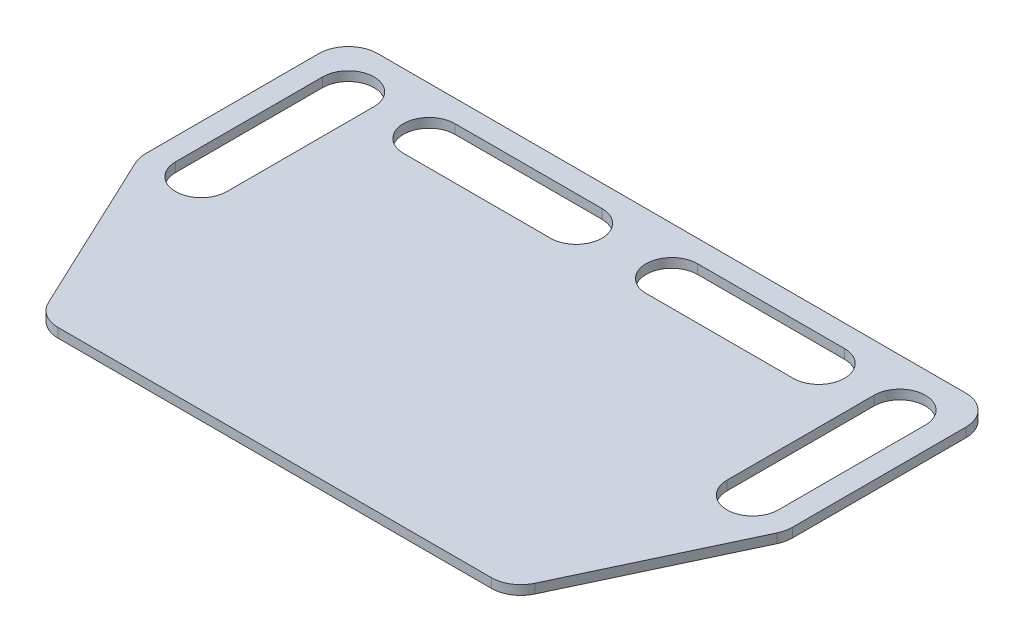
SolidWorks part; units mm, degrees
ref_plane "Front Plane" through (0, 0, 0) normal (0, 0, 1) x (1, 0, 0)
ref_plane "Top Plane" through (0, 0, 0) normal (0, 1, 0) x (1, 0, 0)
ref_plane "Right Plane" through (0, 0, 0) normal (1, 0, 0) x (0, 0, -1)
sketch "Sketch1" plane through (0, 0, 0) normal (0, 1, 0) x (1, 0, 0)
  line L0 (-187.5, 127.5) -> (-187.5, 27.5) construction
  line L1 (-147.3079, -110) -> (147.3079, -110)
  line L2 (-165.4043, -98.5159) -> (-218.0964, 13.4548)
  line L3 (-200, 160) -> (200, 160)
  line L4 (165.4043, -98.5159) -> (218.0964, 13.4548)
  line L5 (220, 21.9707) -> (220, 140)
  line L7 (-170, 127.5) -> (-170, 27.5)
  line L8 (-205, 127.5) -> (-205, 27.5)
  line L9 (-132.5, 127.5) -> (-32.5, 127.5) construction
  line L10 (-132.5, 145) -> (-32.5, 145)
  line L11 (-132.5, 110) -> (-32.5, 110)
  line L12 (-205, 77.5) -> (-170, 77.5) construction
  line L13 (-82.5, 110) -> (-82.5, 145) construction
  line L14 (-205, 77.5) -> (-220, 77.5) construction
  line L15 (-82.5, 145) -> (-82.5, 160) construction
  line L16 (187.5, 127.5) -> (187.5, 27.5) construction
  line L17 (205, 127.5) -> (205, 27.5)
  line L18 (170, 127.5) -> (170, 27.5)
  line L19 (170, 77.5) -> (205, 77.5) construction
  line L20 (32.5, 127.5) -> (132.5, 127.5) construction
  line L21 (-150, -90) -> (150, -90) construction
  line L22 (-150, -90) -> (-150, 90) construction
  line L23 (-150, 90) -> (150, 90) construction
  line L24 (150, -90) -> (150, 90) construction
  line L25 (-150, -90) -> (150, 90) construction
  line L26 (-150, 90) -> (150, -90) construction
  line L27 (32.5, 145) -> (132.5, 145)
  line L28 (32.5, 110) -> (132.5, 110)
  line L29 (82.5, 145) -> (82.5, 110) construction
  line L30 (-170, 127.5) -> (-150, 127.5) construction
  line L32 (-15, 127.5) -> (0, 127.5) construction
  line L33 (0, 160) -> (0, 90) construction
  line L34 (15, 127.5) -> (0, 127.5) construction
  line L35 (-220, 21.9707) -> (-220, 140)
  arc A0 (-170, 127.5) -> (-205, 127.5) centre (-187.5, 127.5) ccw
  arc A1 (-205, 27.5) -> (-170, 27.5) centre (-187.5, 27.5) ccw
  arc A2 (-132.5, 145) -> (-132.5, 110) centre (-132.5, 127.5) ccw
  arc A3 (-32.5, 110) -> (-32.5, 145) centre (-32.5, 127.5) ccw
  arc A4 (205, 127.5) -> (170, 127.5) centre (187.5, 127.5) ccw
  arc A5 (170, 27.5) -> (205, 27.5) centre (187.5, 27.5) ccw
  arc A6 (-220, 140) -> (-200, 160) centre (-200, 140) cw
  arc A7 (-218.0964, 13.4548) -> (-220, 21.9707) centre (-200, 21.9707) cw
  arc A8 (220, 140) -> (200, 160) centre (200, 140) ccw
  arc A9 (-147.3079, -110) -> (-165.4043, -98.5159) centre (-147.3079, -90) cw
  arc A10 (32.5, 145) -> (32.5, 110) centre (32.5, 127.5) ccw
  arc A11 (132.5, 110) -> (132.5, 145) centre (132.5, 127.5) ccw
  arc A12 (165.4043, -98.5159) -> (147.3079, -110) centre (147.3079, -90) cw
  arc A13 (220, 21.9707) -> (218.0964, 13.4548) centre (200, 21.9707) cw
  point P0 (0, 0)
  point P4 (-220, 17.5)
  point P8 (-187.5, 77.5)
  point P15 (-82.5, 127.5)
  point P24 (-150, 127.5)
  point P29 (187.5, 77.5)
  point P34 (-15, 127.5)
  point P37 (0, 0)
  point P53 (-160, -110)
  point P56 (82.5, 127.5)
  point P63 (150, 127.5)
  point P64 (15, 127.5)
  point P76 (160, -110)
  point P79 (220, 17.5)
  dimension "D12" = 20
  dimension "D13" = 10
  dimension "D14" = 20
  dimension "D15" = 10
  dimension "D20" = 20
  dimension "D21" = 20
  dimension "D22" = 20
  dimension "D23" = 20
  dimension "D1" = 20
  dimension "D2" = 20
  dimension "D3" = 15
  dimension "D4" = 35
  dimension "D5" = 20
  dimension "D6" = 15
  dimension "D7" = 15
  dimension "D8" = 300
  dimension "D9" = 180
  dimension "D10" = 20
  dimension "D11" = 20
  dimension "D16" = 100
  dimension "D17" = 100
  dimension "D18" = 10
  dimension "D19" = 10
  dimension "D24" = 20
extrude "Boss-Extrude1" add sketch "Sketch1" along normal blind 6.35
